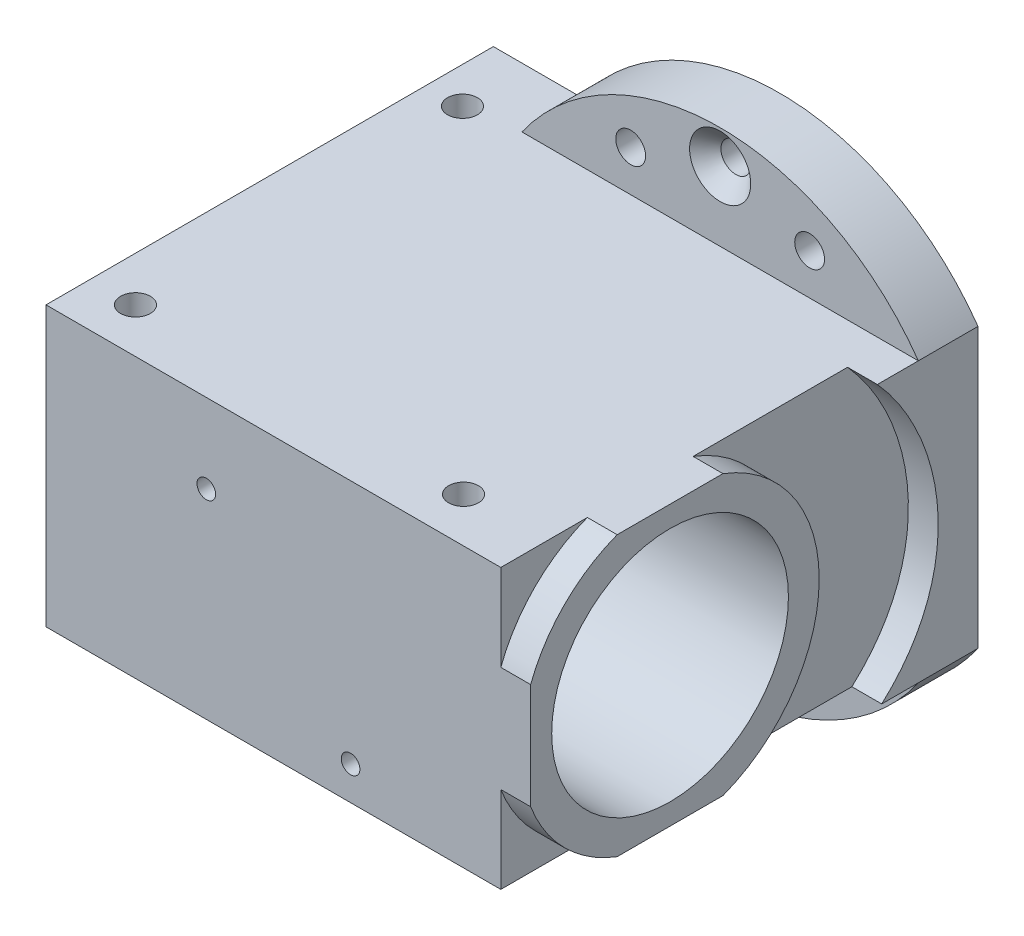
SolidWorks part; units mm, degrees
material "AISI 316 Annealed Stainless Steel Bar (SS)"
ref_plane "Front Plane" through (0, 0, 0) normal (0, 0, 1) x (1, 0, 0)
ref_plane "Top Plane" through (0, 0, 0) normal (0, 1, 0) x (1, 0, 0)
ref_plane "Right Plane" through (0, 0, 0) normal (1, 0, 0) x (0, 0, -1)
sketch "Sketch1" plane through (0, 0, 0) normal (0, 0, 1) x (1, 0, 0)
  line L1 (-32.5, -18.7) -> (32.5, -18.7)
  line L2 (-32.5, -18.7) -> (-32.5, 18.7)
  line L3 (-32.5, 18.7) -> (32.5, 18.7)
  line L4 (32.5, -18.7) -> (32.5, 18.7)
  line L5 (-32.5, -18.7) -> (32.5, 18.7) construction
  line L6 (-32.5, 18.7) -> (32.5, -18.7) construction
  point P0 (0, 0)
  dimension "D1" = 65
  dimension "D2" = 37.4
extrude "Boss-Extrude1" add sketch "Sketch1" along normal blind 60
sketch "Sketch2" plane through (32.5, 0, 0) normal (1, 0, 0) x (0, 0, -1)
  line L0 (-60, 18.7) -> (0, 18.7) construction
  line L1 (-60, -18.7) -> (-60, 18.7) construction
  circle A0 centre (-41.3, 0) radius 15.875
  dimension "D3" = 31.75
  dimension "D1" = 18.7
  dimension "D2" = 18.7
extrude "Cut-Extrude1" cut sketch "Sketch2" against normal through all
hole_wizard "Ø1.0mm Dowel Hole1" positions "Sketch4" profile "Sketch5" hole size "Ø1.0" standard "ANSI Metric"
sketch "Sketch4" plane through (0, 0, 60) normal (0, 0, 1) x (1, 0, 0)
  line L0 (32.5, 18.7) -> (-32.5, 18.7) construction
  line L1 (-32.5, 18.7) -> (-32.5, -18.7) construction
  line L2 (32.5, -18.7) -> (32.5, 18.7) construction
  line L3 (-32.5, -18.7) -> (32.5, -18.7) construction
  point P0 (-11, 8.07)
  point P2 (8.35, -14.2)
  dimension "D1" = 10.63
  dimension "D2" = 21.5
  dimension "D3" = 24.15
  dimension "D4" = 4.5
sketch "Sketch5" plane through (-11, 8.07, 60) normal (1, 0, 0) x (0, -1, 0)
  line L0 (0, 0) -> (0, 5.7511)
  line L1 (0, 5.7511) -> (1.25, 5)
  line L2 (1.25, 5) -> (1.25, 0)
  line L5 (1.25, 0) -> (0, 0)
  line L10 (0, 5.7511) -> (-1.25, 5) construction
  line L11 (0, -6.35) -> (0, 107.95) construction
  dimension "Hole Dia." = 2.5
  dimension "Hole Depth" = 5
  dimension "Drill Angle" = 118
hole_wizard "Ø1.0mm Dowel Hole2" positions "Sketch18" profile "Sketch19" hole size "Ø1.0" standard "ANSI Metric"
sketch "Sketch18" plane through (0, -18.7, 0) normal (0, -1, 0) x (-1, 0, 0)
  line L0 (-32.5, -60) -> (-32.5, 0) construction
  line L1 (32.5, -60) -> (-32.5, -60) construction
  point P0 (-26.5, -54)
  dimension "D1" = 6
  dimension "D2" = 6
sketch "Sketch19" plane through (26.5, -18.7, 54) normal (1, 0, 0) x (0, 0, -1)
  line L0 (0, 0) -> (0, 5.9914)
  line L1 (0, 5.9914) -> (1.65, 5)
  line L2 (1.65, 5) -> (1.65, 0)
  line L5 (1.65, 0) -> (0, 0)
  line L10 (0, 5.9914) -> (-1.65, 5) construction
  line L11 (0, -6.35) -> (0, 107.95) construction
  dimension "Hole Dia." = 3.3
  dimension "Hole Depth" = 5
  dimension "Drill Angle" = 118
pattern_linear "LPattern2" count 2 spacing 41.9 along (-1, 0, 0) of "Ø1.0mm Dowel Hole2"
pattern_linear "LPattern3" count 2 spacing 35.5 along (0, 0, -1) of "Ø1.0mm Dowel Hole2"
sketch "Sketch20" plane through (0, 0, 0) normal (1, 0, 0) x (0, 0, -1)
  circle A0 centre (-41.3, 0) radius 12.7
  circle A1 centre (-41.3, 0) radius 15.875 construction
  circle A2 centre (-41.3, 0) radius 15.875
  dimension "D1" = 25.4
extrude "Boss-Extrude6" add sketch "Sketch20" along normal mid plane 14
sketch "Sketch23" plane through (32.5, 0, 0) normal (1, 0, 0) x (0, 0, -1)
  line L0 (-48.393, 18.7) -> (-34.207, 18.7)
  line L1 (-60, 18.7) -> (0, 18.7) construction
  line L2 (-60, 7.093) -> (-60, -7.093)
  line L3 (-60, -18.7) -> (-60, 18.7) construction
  line L4 (-48.393, -18.7) -> (-34.207, -18.7)
  line L5 (-60, -18.7) -> (0, -18.7) construction
  line L11 (0, -18.7) -> (0, 18.7)
  line L13 (0, 18.7) -> (-60, 18.7)
  line L14 (-60, 18.7) -> (-60, -18.7)
  line L15 (-60, -18.7) -> (0, -18.7)
  line L18 (-13.4977, 18.7) -> (-60, 18.7)
  line L19 (-60, 18.7) -> (-60, -18.7)
  line L20 (-60, -18.7) -> (-12.913, -18.7)
  arc A0 (-48.393, 18.7) -> (-60, 7.093) centre (-41.3, 0) ccw
  arc A1 (-60, -7.093) -> (-48.393, -18.7) centre (-41.3, 0) ccw
  arc A2 (-34.207, -18.7) -> (-34.207, 18.7) centre (-41.3, 0) ccw
  circle A3 centre (-41.3, 0) radius 15.875
  spline S0 degree 3 poles (-13.4977, 18.7) (-4.4895, 8.6997) (-1.1257, -8.0666) (-12.913, -18.7) knots 0 0 0 0 1 1 1 1
  spline S1 degree 1 poles (18.0837, 0.7006) (12.1803, 0.7838) knots 0 0 1 1
  line M16 (0, 18.7) -> (-60, 18.7)
  line M17 (-60, 18.7) -> (-60, -18.7)
  line M18 (-60, -18.7) -> (0, -18.7)
  dimension "D1" = 40
  dimension "D2" = 0
extrude "Cut-Extrude2" cut sketch "Sketch23" against normal blind 4 contours A0 M16 M17 | A1 M17 M18 | S0 A2 M16 M18
sketch "Sketch24" plane through (0, 0, 0) normal (0, 0, -1) x (-1, 0, 0)
  line L4 (-32.5, 18.7) -> (-32.5, -18.7)
  line L5 (-32.5, -18.7) -> (32.5, -18.7)
  line L6 (32.5, -18.7) -> (32.5, 18.7)
  line L7 (32.5, 18.7) -> (-32.5, 18.7)
  line L9 (-32.5, -18.7) -> (20.6624, -18.7)
  line L11 (20.6624, 18.7) -> (-32.5, 18.7)
  arc A0 (20.6624, 18.7) -> (-32.5, 18.7) centre (-5.9188, 0) ccw
  arc A1 (-32.5, -18.7) -> (20.6624, -18.7) centre (-5.9188, 0) ccw
  circle A3 centre (-17.9188, 24.2) radius 2
  circle A4 centre (6.0812, 24.2) radius 2
  circle A5 centre (6.0812, -24.2) radius 2
  circle A7 centre (-17.9188, -24.2) radius 2
  dimension "D1" = 65
  dimension "D3" = 14.5812
  dimension "D4" = 14.5812
  dimension "D5" = 4
  dimension "D6" = 5.5
  dimension "D7" = 5.5
  dimension "D2" = 0
extrude "Boss-Extrude7" add sketch "Sketch24" against normal blind 8
hole_wizard "CSK for M3.5 Flat Head Machine Screw2" positions "Sketch31" profile "Sketch32" countersink size "M3.5" standard "ANSI Metric" end condition through all
sketch "Sketch31" plane through (0, 0, 8) normal (0, 0, 1) x (1, 0, 0)
  circle A0 centre (-6.0812, 24.2) radius 2 construction
  circle A1 centre (17.9188, 24.2) radius 2 construction
  point P0 (5.9188, 28)
  dimension "D1" = 3.8
  dimension "D2" = 12
sketch "Sketch32" plane through (5.9188, 28, 8) normal (1, 0, 0) x (0, -1, 0)
  line L0 (0, 0) -> (0, 8)
  line L1 (0, 8) -> (2, 8)
  line L2 (2, 8) -> (2, 2.1)
  line L3 (2, 2.1) -> (4.1, 0)
  line L5 (4.1, 0) -> (0, 0)
  line L6 (-2, 2.1) -> (-4.1, 0) construction
  line L11 (0, -6.35) -> (0, 107.95) construction
  dimension "Thru Hole Dia." = 4
  dimension "Thru Hole Depth" = 8
  dimension "Near C'Sink Dia." = 8.2
  dimension "Near C'Sink Angle" = 90
mirror "Mirror1" about plane through (0, 0, 0) normal (0, 1, 0) of "CSK for M3.5 Flat Head Machine Screw2"
hole_wizard "Ø4.0mm Dowel Hole2" positions "Sketch42" profile "Sketch43" hole size "Ø4.0" standard "ANSI Metric"
sketch "Sketch42" plane through (0, 18.7, 0) normal (0, 1, 0) x (1, 0, 0)
  line L0 (28.5, -60) -> (-32.5, -60) construction
  line L1 (-32.5, -60) -> (-32.5, 0) construction
  point P0 (-26.5, -54)
  point P2 (17.5, -54)
  point P4 (-27.6417, -9)
  dimension "D1" = 6
  dimension "D2" = 6
  dimension "D3" = 44
  dimension "D4" = 45
sketch "Sketch43" plane through (-26.5, 18.7, 54) normal (1, 0, 0) x (0, 0, 1)
  line L0 (0, 0) -> (0, 5.2017)
  line L1 (0, 5.2017) -> (2, 4)
  line L2 (2, 4) -> (2, 0)
  line L5 (2, 0) -> (0, 0)
  line L10 (0, 5.2017) -> (-2, 4) construction
  line L11 (0, -6.35) -> (0, 107.95) construction
  dimension "Hole Dia." = 4
  dimension "Hole Depth" = 4
  dimension "Drill Angle" = 118
